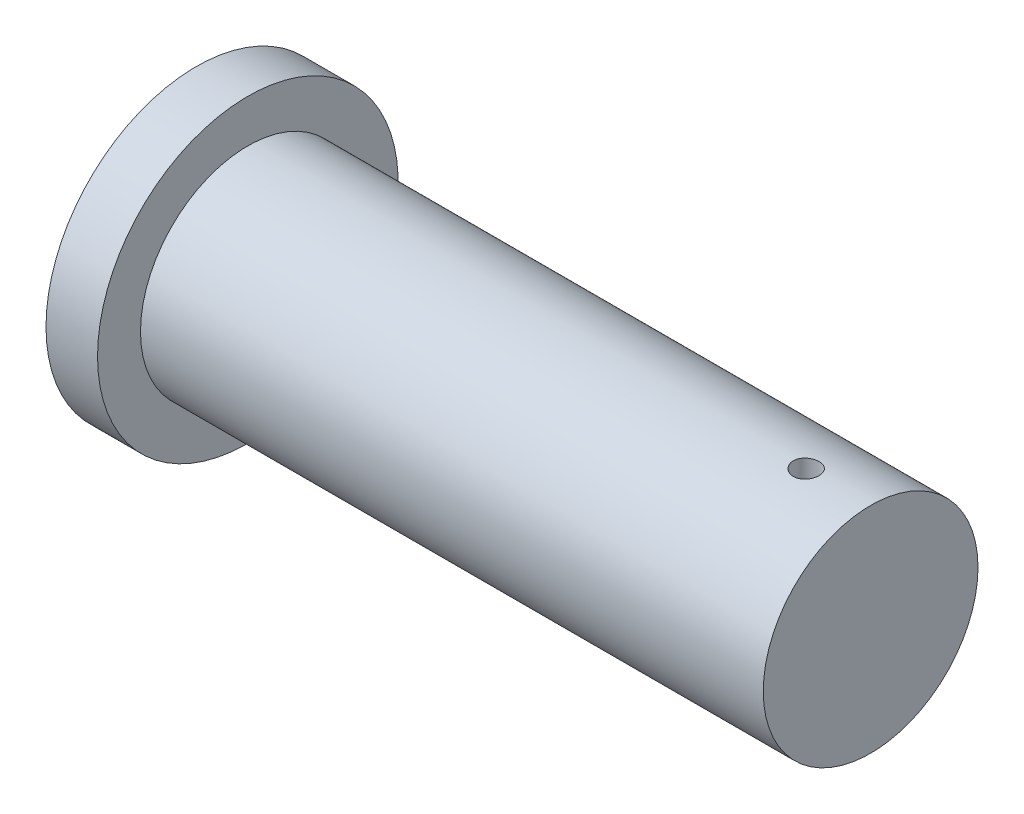
SolidWorks part; units mm, degrees
ref_plane "Front Plane" through (0, 0, 0) normal (0, 0, 1) x (1, 0, 0)
ref_plane "Top Plane" through (0, 0, 0) normal (0, 1, 0) x (1, 0, 0)
ref_plane "Right Plane" through (0, 0, 0) normal (1, 0, 0) x (0, 0, -1)
sketch "Sketch1" plane through (0, 0, 0) normal (0, 0, 1) x (1, 0, 0)
  line L0 (0, 0) -> (0, 25)
  line L1 (0, 25) -> (-145, 25)
  line L2 (-145, 25) -> (-145, 35)
  line L3 (-145, 35) -> (-157, 35)
  line L4 (-157, 35) -> (-157, 0)
  line L5 (-157, 0) -> (0, 0)
  dimension "D1" = 25
  dimension "D2" = 35
  dimension "D3" = 12
  dimension "D4" = 157
revolve "Revolve1" add sketch "Sketch1" angle 360 about L5
sketch "Sketch2" plane through (0, 0, 0) normal (0, 1, 0) x (1, 0, 0)
  line L0 (-145, -25) -> (-145, 25) construction
  circle A0 centre (-15, 0) radius 3
  point P4 (0, 0)
  dimension "D1" = 6
  dimension "D2" = 130
extrude "Cut-Extrude1" cut sketch "Sketch2" against normal through all both and the other way through all
